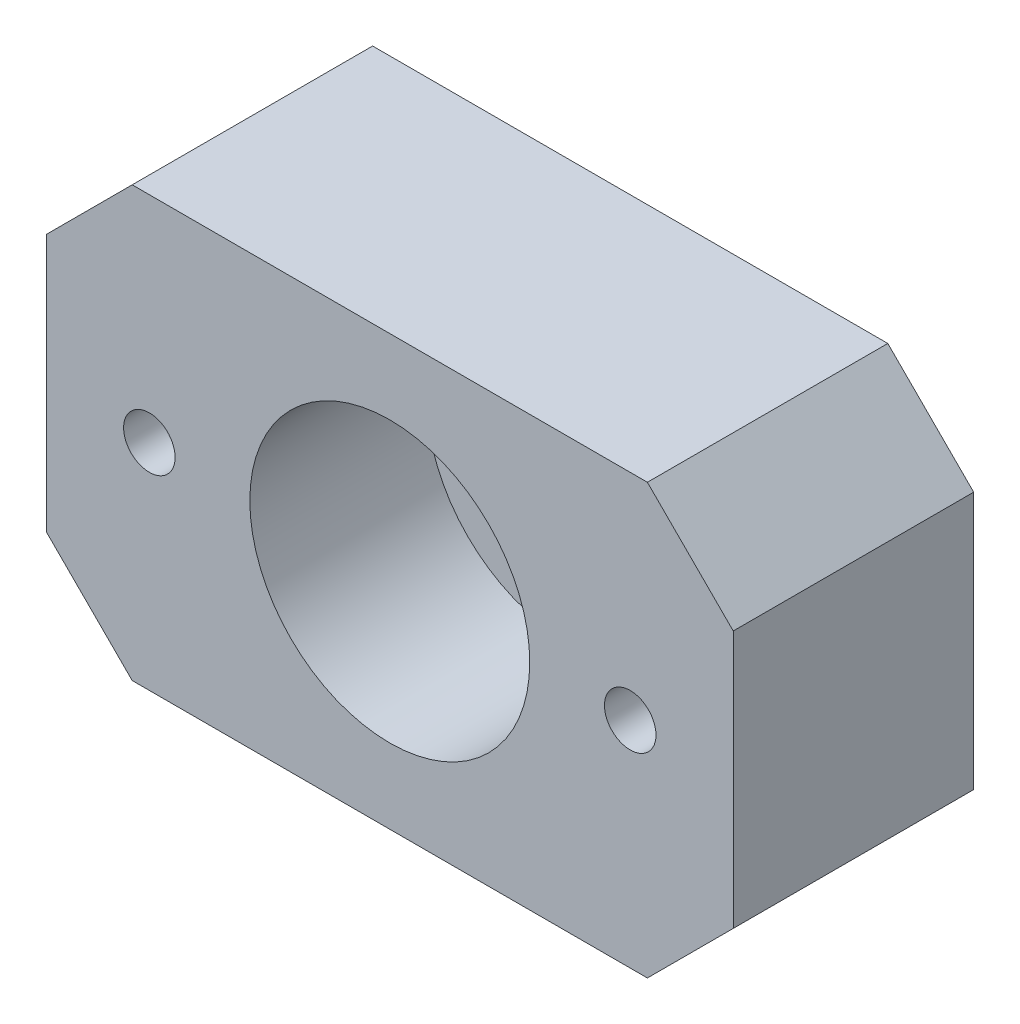
SolidWorks part; units mm, degrees
ref_plane "Front Plane" through (0, 0, 0) normal (0, 0, 1) x (1, 0, 0)
ref_plane "Top Plane" through (0, 0, 0) normal (0, 1, 0) x (1, 0, 0)
ref_plane "Right Plane" through (0, 0, 0) normal (1, 0, 0) x (0, 0, -1)
sketch "Sketch1" plane through (0, 0, 0) normal (0, 0, 1) x (1, 0, 0)
  line L1 (0, 0) -> (40, 0)
  line L2 (0, 0) -> (0, 25)
  line L3 (0, 25) -> (40, 25)
  line L4 (40, 0) -> (40, 25)
  dimension "D1" = 40
  dimension "D2" = 25
extrude "Boss-Extrude1" add sketch "Sketch1" along normal blind 14
sketch "Sketch2" plane through (0, 0, 14) normal (0, 0, 1) x (1, 0, 0)
  line L0 (0, 25) -> (0, 0) construction
  line L1 (40, 25) -> (0, 25) construction
  circle A0 centre (20, 12.5) radius 8.15
  point P5 (0, 12.5)
  point P9 (20, 25)
  dimension "D1" = 16.3
extrude "Cut-Extrude1" cut sketch "Sketch2" against normal blind 10.3
sketch "Sketch3" plane through (0, 0, 3.7) normal (0, 0, 1) x (1, 0, 0)
  circle A0 centre (20, 12.5) radius 2.65
  dimension "D1" = 5.3
extrude "Cut-Extrude2" cut sketch "Sketch3" against normal up to next
sketch "Sketch4" plane through (0, 0, 14) normal (0, 0, 1) x (1, 0, 0)
  line L0 (40, 0) -> (40, 25) construction
  line L1 (0, 25) -> (0, 0) construction
  circle A0 centre (6, 12.5) radius 1.5
  circle A1 centre (34, 12.5) radius 1.5
  circle A2 centre (20, 12.5) radius 8.15 construction
  circle A3 centre (20, 12.5) radius 8.15 construction
  point P11 (40, 12.5)
  point P15 (0, 12.5)
  dimension "D1" = 14
  dimension "D2" = 14
  dimension "D3" = 3
extrude "Cut-Extrude3" cut sketch "Sketch4" against normal up to next
chamfer "Chamfer1" distance 5 angle 45 4 edges at (40, 0, 7) (0, 0, 7) (0, 25, 7) (40, 25, 7)
